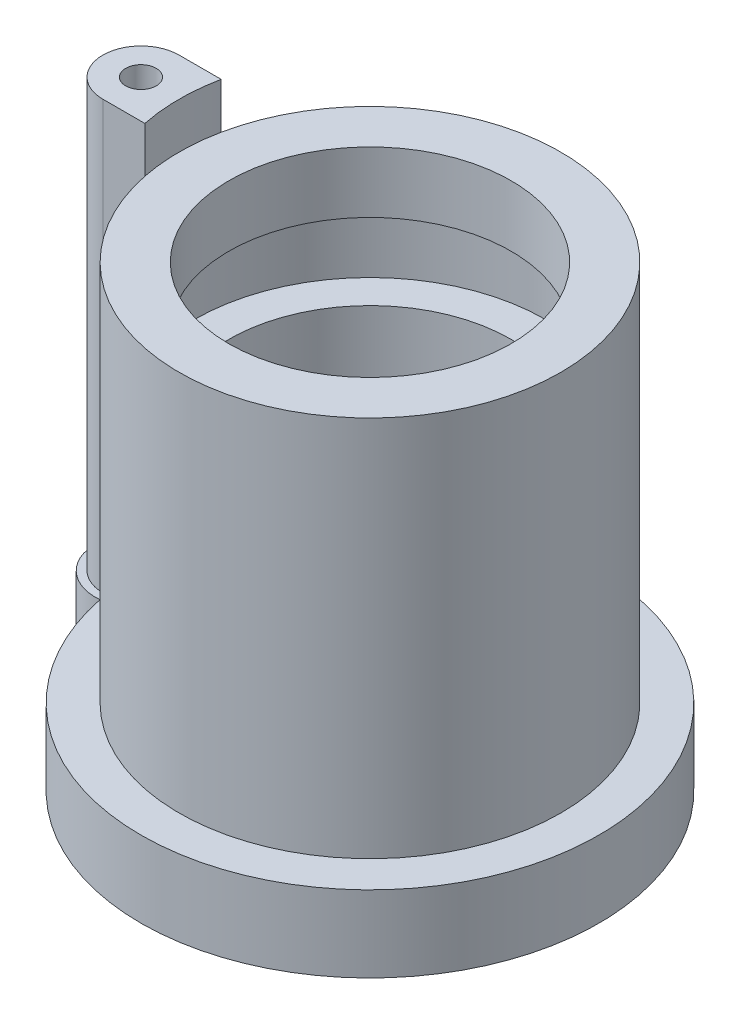
SolidWorks part; units mm, degrees
ref_plane "Front Plane" through (0, 0, 0) normal (0, 0, 1) x (1, 0, 0)
ref_plane "Top Plane" through (0, 0, 0) normal (0, 1, 0) x (1, 0, 0)
ref_plane "Right Plane" through (0, 0, 0) normal (1, 0, 0) x (0, 0, -1)
sketch "Sketch1" plane through (0, 0, 0) normal (0, 1, 0) x (1, 0, 0)
  circle A0 centre (0, 0) radius 9 construction
  circle A1 centre (0, 0) radius 12 construction
  circle A2 centre (0, 0) radius 11.5
  circle A3 centre (0, 0) radius 12.5
  circle A4 centre (0, 0) radius 9.25
  dimension "D1" = 24
  dimension "D2" = 18
  dimension "D3" = 23
  dimension "D4" = 25
  dimension "D5" = 18.5
extrude "Boss-Extrude1" add sketch "Sketch1" along normal blind 25 contours A2 A4 | A3 A2
ref_plane "Plane1" through (0, 21, 0) normal (0, 1, 0) x (1, 0, 0)
sketch "Sketch2" plane through (0, 21, 0) normal (0, 1, 0) x (1, 0, 0)
  circle A0 centre (0, 0) radius 9.25
  circle A1 centre (0, 0) radius 11.5
  dimension "D1" = 18.5
  dimension "D2" = 23
extrude "Cut-Extrude1" cut sketch "Sketch2" against normal blind 5
sketch "Sketch3" plane through (0, 0, 0) normal (0, -1, 0) x (1, 0, 0)
  line L0 (0, 0) -> (-15, 0) construction
  circle A0 centre (0, 0) radius 15
  circle A1 centre (-15, 0) radius 3
  dimension "D1" = 30
  dimension "D3" = 6
  dimension "D2" = 15
extrude "Boss-Extrude2" add sketch "Sketch3" along normal blind 5
sketch "Sketch4" plane through (0, 0, 0) normal (0, 1, 0) x (1, 0, 0)
  line L0 (0, 0) -> (-15, 0) construction
  line L1 (-15, 2.5) -> (-12.2474, 2.5)
  line L2 (-12.2474, 2.5) -> (-12.2474, -2.5)
  line L3 (-12.2474, -2.5) -> (-15, -2.5)
  circle A0 centre (-15, 0) radius 1
  circle A1 centre (-15, 0) radius 2.5
  circle A2 centre (0, 0) radius 12.5 construction
  dimension "D1" = 2
  dimension "D3" = 5
  dimension "D2" = 15
extrude "Boss-Extrude5" add sketch "Sketch4" along normal blind 28
